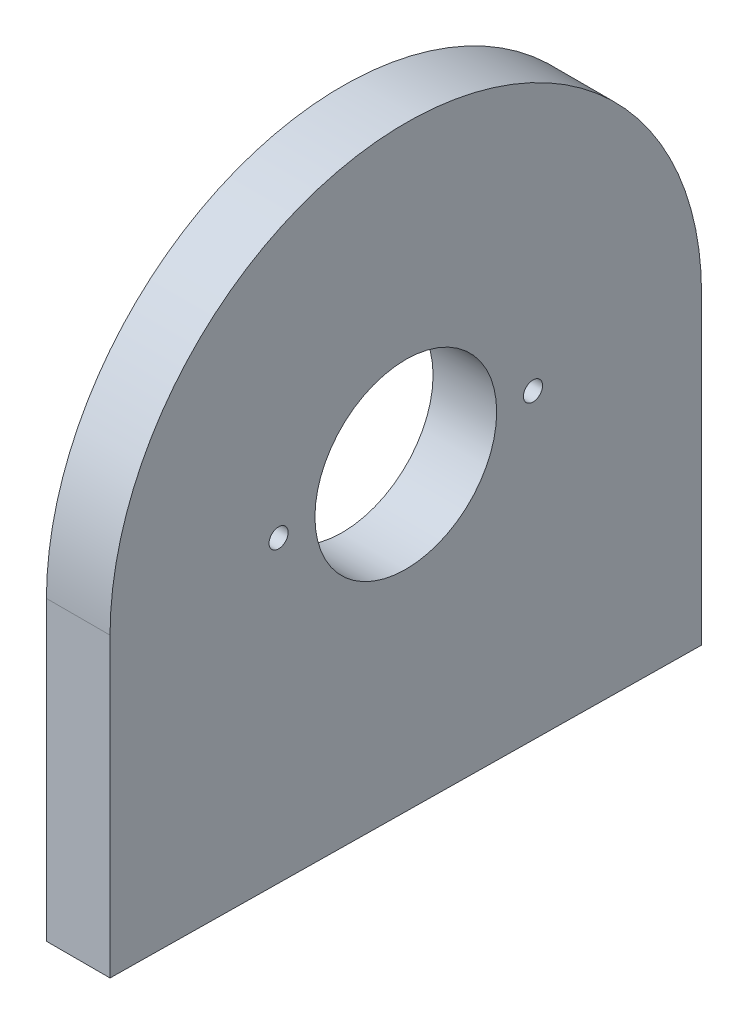
SolidWorks part; units mm, degrees
material "6061-T6 (SS)"
ref_plane "Front Plane" through (0, 0, 0) normal (0, 0, 1) x (1, 0, 0)
ref_plane "Top Plane" through (0, 0, 0) normal (0, 1, 0) x (1, 0, 0)
ref_plane "Right Plane" through (0, 0, 0) normal (1, 0, 0) x (0, 0, -1)
sketch "Sketch1" plane through (0, 0, 0) normal (1, 0, 0) x (0, 0, -1)
  line L0 (-46.5, 0) -> (-46.5, -46.6807)
  line L1 (-46.5, -46.6807) -> (46.5, -47.8585)
  line L2 (46.5, -47.8585) -> (46.5, 0)
  circle A0 centre (0, 0) radius 14.2875
  arc A1 (-46.5, 0) -> (46.5, 0) centre (0, 0) cw
  arc A2 (-46.5, 0) -> (46.5, 0) centre (0, 0) ccw construction
  circle A3 centre (20, 0) radius 1.5
  circle A4 centre (-20, 0) radius 1.5
  dimension "D1" = 28.575
  dimension "D2" = 46.5
  dimension "D3" = 20
  dimension "D4" = 20
  dimension "D5" = 3
  dimension "D6" = 3
extrude "Boss-Extrude1" add sketch "Sketch1" along normal blind 10
